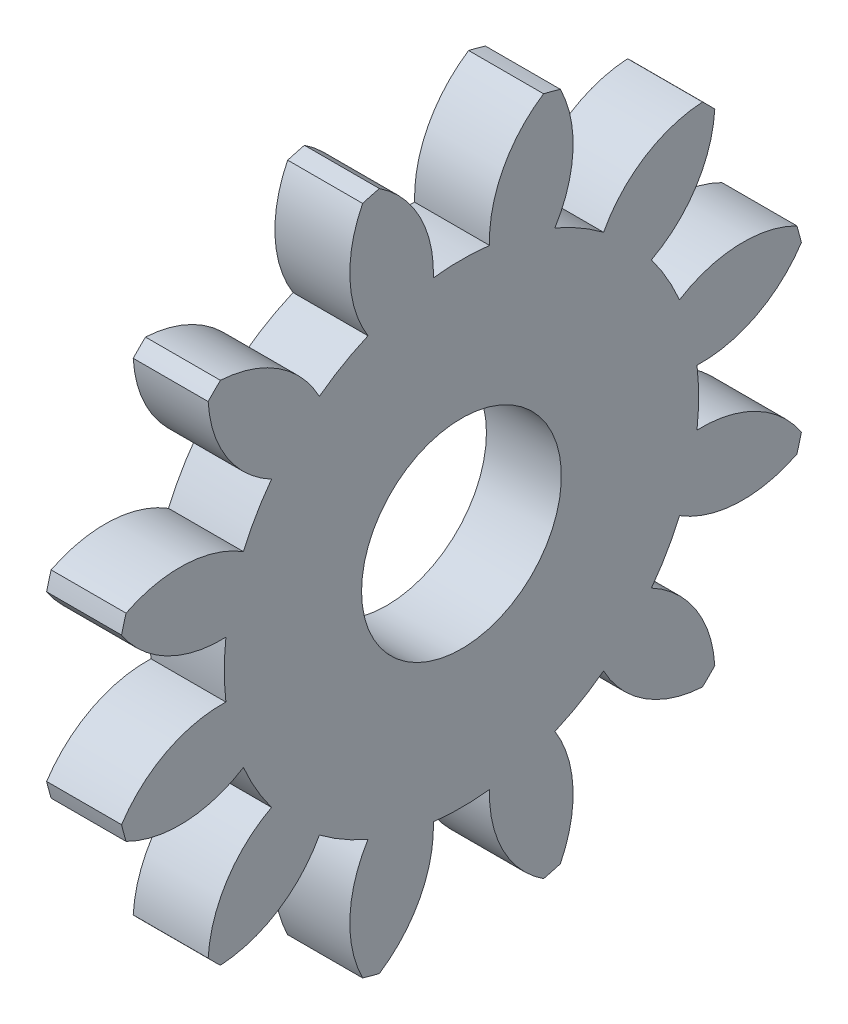
SolidWorks part; units mm, degrees
material "Zinc AC41A Alloy, As Cast"
ref_plane "Plane1" through (0, 0, 0) normal (0, 0, 1) x (1, 0, 0)
ref_plane "Plane2" through (0, 0, 0) normal (0, 1, 0) x (1, 0, 0)
ref_plane "Plane3" through (0, 0, 0) normal (1, 0, 0) x (0, 0, -1)
sketch "HoldingSke" plane through (0, 0, 0) normal (0, 1, 0) x (1, 0, 0)
  line L0 (0, 0) -> (0.9781, -0.2079)
  line L1 (-15, 0) -> (100, 0) construction
  line L2 (0, 0) -> (-2.1039, 2.3779)
  line L3 (0, 0) -> (-11.863, 4.5341)
  line L4 (0, 0) -> (8.4473, 1.7955)
  line L5 (0, 0) -> (-46.8476, -17.4728)
  line L6 (0, 0) -> (-1.2434, -0.839)
  line L7 (-2.1039, 2.3779) -> (8.6586, 51.2059)
  line L8 (-76.2, 54.61) -> (-75.5, 54.61)
  line L9 (-71.009, 38.7566) -> (-53.1078, 45.2721)
  line L10 (-76.2, 71.12) -> (104.1128, 71.12)
  line L11 (0, 0) -> (-1.5, 0)
  line L12 (-76.2, 101.6) -> (-76.162, 101.6)
  line L13 (24.9733, 27.94) -> (52.9518, 28.4284)
  line L14 (24.9733, 27.94) -> (24.9743, 27.94)
  line L15 (24.9733, 27.94) -> (100.4006, 29.5858)
  line L16 (-63.627, -1) -> (-12.827, -1)
  circle A0 centre (0, 0) radius 2
  circle A1 centre (0, 0) radius 4.749
  circle A2 centre (0, 0) radius 37.5
  circle A3 centre (0, 0) radius 2
  dimension "MHD" = 9.498
  dimension "Hub_dia" = 75
  dimension "Bore" = 4
  dimension "MBD" = 4
  dimension "Num_teeth" = 12
  dimension "Pitch" = 1
  dimension "Overall_len" = 50
  dimension "Show_teeth" = 12
  dimension "Thickness" = 1.5
  dimension "OAL" = 50.0001
  dimension "T_dim" = 0.7
  dimension "Ap" = 20
  dimension "H" = 19.05
  dimension "Pitch_radius" = 180.3128
  dimension "Width" = 1.5
  dimension "Backlash" = 0.038
  dimension "Addendum_fac" = 1
  dimension "Dedendum_fac" = 1.25
  dimension "Clearance_fac" = 0.25
  dimension "Dedendum_add" = 0.001
  dimension "Module" = 1
sketch "BasProSke" plane through (0, 0, 0) normal (0, 1, 0) x (1, 0, 0)
  line L0 (-10, 0) -> (60, 0) construction
  line L1 (0, 0) -> (0, 7)
  line L2 (0, 0) -> (1.5, 0)
  line L3 (1.5, 0) -> (1.5, 7)
  line L4 (1.5, 7) -> (0, 7)
  dimension "Thickness" = 1.5
  dimension "Diameter" = 14
revolve "Base-Revolve" add sketch "BasProSke" angle 360 about L0
sketch "TooCutSke" plane through (0, 0, 0) normal (1, 0, 0) x (0, 0, -1)
  line L1 (0, 0) -> (0, 107) construction
  line L2 (0, 0) -> (-0.8496, 5.9395) construction
  line L3 (0, 0) -> (-3.0836, 11.5081) construction
  line L4 (-0.8496, 5.9395) -> (-1.5418, 5.7541) construction
  arc A0 (0.5622, 4.7156) -> (-0.5622, 4.7156) centre (0, 0) ccw
  arc A1 (1.6729, 6.8233) -> (-1.6729, 6.8233) centre (0, 0) ccw
  circle A2 centre (0, 0) radius 6 construction
  circle A3 centre (0, 0) radius 5.6382 construction
  arc A4 (-0.5622, 4.7156) -> (-1.6729, 6.8233) centre (-2.9608, 4.7982) ccw
  arc A5 (1.6729, 6.8233) -> (0.5622, 4.7156) centre (2.9608, 4.7982) ccw
  dimension "Root_dia" = 9.498
  dimension "Overcut_dia" = 14.0508
  dimension "Pitch_dia" = 12
  dimension "Base_dia" = 11.2763
  dimension "Flank_rad" = 2.4
  dimension "Half_ang" = 15
  dimension "Half_CT" = 0.7167
extrude "ToothCut" cut sketch "TooCutSke" along normal through all
fillet "Breaks" [suppressed] radius 0.02
fillet "RootFillets" [suppressed] radius 0.251
pattern_circular "TeethCuts" count 12 every 30 about axis through (-10, 0, 0) along (1, 0, 0) of "ToothCut", "RootFillets", "Breaks"
sketch "HubNeaOneSke" plane through (0, 0, 0) normal (-1, 0, 0) x (0, 0, 1)
  circle A0 centre (0, 0) radius 4.749
  dimension "Diameter" = 9.498
extrude "HubNearOne" [suppressed] add sketch "HubNeaOneSke" along normal blind 48.5001
sketch "HubNeaBotSke" plane through (0, 0, 0) normal (-1, 0, 0) x (0, 0, 1)
  circle A0 centre (0, 0) radius 4.749
  dimension "Diameter" = 9.498
extrude "HubNearBoth" [suppressed] add sketch "HubNeaBotSke" along normal blind 24.25
ref_plane "FarPln" through (1.5, 0, 0) normal (1, 0, 0) x (0, 0, -1)
sketch "HubFarSke" plane through (1.5, 0, 0) normal (1, 0, 0) x (0, 0, -1)
  circle A0 centre (0, 0) radius 4.749
  dimension "Diameter" = 9.498
extrude "HubFar" [suppressed] add sketch "HubFarSke" along normal blind 24.25
sketch "BorSke" plane through (0, 0, 0) normal (1, 0, 0) x (0, 0, -1)
  circle A0 centre (0, 0) radius 2
  dimension "Diameter" = 4
extrude "Bore" cut sketch "BorSke" along normal mid plane 100.0001
sketch "KeySke" plane through (0, 0, 0) normal (1, 0, 0) x (0, 0, -1)
  line L0 (-0.8, 0) -> (-0.8, 2.7)
  line L1 (-0.8, 2.7) -> (0.8, 2.7)
  line L2 (0.8, 2.7) -> (0.8, 0)
  line L3 (0, 0) -> (0, 34) construction
  line L4 (-0.8, 0) -> (0.8, 0)
  dimension "Offset" = 2.7
  dimension "Width" = 1.6
extrude "Keyway" [suppressed] cut sketch "KeySke" along normal mid plane 100.0001
pattern_circular "Keyway2" [suppressed] count 2 every 90 about axis through (-10, 0, 0) along (1, 0, 0)
equation "' \"Module@HoldingSke\" = 6.35"
equation "' \"Num_teeth@HoldingSke\" = 12"
equation "' \"Ap@HoldingSke\" =  20"
equation "' \"Ap@HoldingSke\" = 20"
equation "' \"Width@HoldingSke\" = 0.5 * 25.4"
equation "' \"Hub_dia@HoldingSke\"= 1 * 25.4"
equation "' \"Hub_dia@HoldingSke\" = 1 * 25.4"
equation "' \"Overall_len@HoldingSke\" = 1.0 * 25.4"
equation "' \"Bore@HoldingSke\" = 0.75 * 25.4"
equation "' \"T_dim@HoldingSke\" = 0.1 * 25.4"
equation "' \"Width@KeySke\" = 0.25 * 25.4"
equation "' \"Show_teeth@HoldingSke\" = 13"
equation "' \"Backlash@HoldingSke\" = 0.009 * 25.4"
equation "' \"Addendum_fac@HoldingSke\" = 1.0"
equation "' \"Dedendum_fac@HoldingSke\" = 1.25"
equation "' \"Dedendum_add@HoldingSke\" = 0.00005 * 25.4"
equation "' \"Clearance_fac@HoldingSke\" = 0.25"
equation "\"Pitch@HoldingSke\" = 1 / \"Module@HoldingSke\""
equation "\"Overcut_dia@TooCutSke\" = (\"Num_teeth@HoldingSke\" + 2 * \"Addendum_fac@HoldingSke\") / \"Pitch@HoldingSke\" + 0.002 * 25.4"
equation "\"Pitch_dia@TooCutSke\" = \"Num_teeth@HoldingSke\" / \"Pitch@HoldingSke\""
equation "\"Base_dia@TooCutSke\" = \"Num_teeth@HoldingSke\" / \"Pitch@HoldingSke\" * cos((\"Ap@HoldingSke\"  * 3.14159265 / 180))"
equation "\"Root_dia@TooCutSke\" = (\"Num_teeth@HoldingSke\" + 2) / \"Pitch@HoldingSke\" - 2 * (\"Addendum_fac@HoldingSke\" + \"Dedendum_fac@HoldingSke\") / \"Pitch@HoldingSke\" - \"Dedendum_add@HoldingSke\" * 2"
equation "\"Half_ang@TooCutSke\" = 180 / \"Num_teeth@HoldingSke\""
equation "\"Half_CT@TooCutSke\" = \"Num_teeth@HoldingSke\" / \"Pitch@HoldingSke\" * sin((3.14159265 / 2 / \"Num_teeth@HoldingSke\")) / 2 - 7 * \"Backlash@HoldingSke\" / 4"
equation "\"Flank_rad@TooCutSke\" = \"Num_teeth@HoldingSke\" / \"Pitch@HoldingSke\" / 5"
equation "\"Radius@RootFillets\" = \"Clearance_fac@HoldingSke\" / \"Pitch@HoldingSke\" + \"Dedendum_add@HoldingSke\""
equation "\"Break_rad@Breaks\" = 0.02 / \"Pitch@HoldingSke\""
equation "\"Thickness@HoldingSke\" = \"Width@HoldingSke\""
equation "\"OAL@HoldingSke\" = \"Thickness@HoldingSke\""
equation "\"MHD@HoldingSke\" = (\"Num_teeth@HoldingSke\" + 2) / \"Pitch@HoldingSke\" - 2 * (\"Addendum_fac@HoldingSke\" + \"Dedendum_fac@HoldingSke\")  / \"Pitch@HoldingSke\" - \"Dedendum_add@HoldingSke\" * 2"
equation "\"MBD@HoldingSke\" = (\"Num_teeth@HoldingSke\" + 2) / \"Pitch@HoldingSke\" - 2 * (\"Addendum_fac@HoldingSke\" + \"Dedendum_fac@HoldingSke\")  / \"Pitch@HoldingSke\" - \"Dedendum_add@HoldingSke\" * 2 - 0.002 * 25.4"
equation "\"MHD@HoldingSke\" = ((sgn( \"MHD@HoldingSke\" - \"Hub_dia@HoldingSke\" )-1)*( \"MHD@HoldingSke\" - \"Hub_dia@HoldingSke\" ))/-2+ \"Hub_dia@HoldingSke\""
equation "\"MBD@HoldingSke\" = ((sgn( \"MBD@HoldingSke\" - \"Bore@HoldingSke\" )-1)*( \"MBD@HoldingSke\" - \"Bore@HoldingSke\" ))/-2+ \"Bore@HoldingSke\""
equation "\"OAL@HoldingSke\" = ((sgn( \"OAL@HoldingSke\" - \"Overall_len@HoldingSke\" )+1)*( \"OAL@HoldingSke\" - \"Overall_len@HoldingSke\" ))/2 + \"Overall_len@HoldingSke\" + 0.000002 * 25.4"
equation "\"Num_teeth@TeethCuts\" = int( \"Show_teeth@HoldingSke\" ) + 1"
equation "\"Num_teeth@TeethCuts\" = ((sgn( \"Num_teeth@TeethCuts\" - \"Num_teeth@HoldingSke\" )-1)*( \"Num_teeth@TeethCuts\" - \"Num_teeth@HoldingSke\" ))/-2+ \"Num_teeth@HoldingSke\""
equation "\"Num_teeth@TeethCuts\" = ((sgn( \"Num_teeth@TeethCuts\" - 2.0)+1)*( \"Num_teeth@TeethCuts\" - 2.0))/2 +2.0"
equation "\"Angle@TeethCuts\" = 360.0 / \"Num_teeth@HoldingSke\""
equation "\"Diameter@BasProSke\" = (\"Num_teeth@HoldingSke\" + 2 * \"Addendum_fac@HoldingSke\") / \"Pitch@HoldingSke\""
equation "\"Thickness@BasProSke\"  = \"Thickness@HoldingSke\""
equation "' \"Fillet_rad@BasProSke\" =  \"Thickness@HoldingSke\" * 0.05"
equation "' \"Fillet_rad@BasProSke\" = \"Thickness@HoldingSke\" * 0.05"
equation "\"MHD@HoldingSke\" = ((sgn( \"MHD@HoldingSke\" - \"Root_dia@TooCutSke\" )-1)*( \"MHD@HoldingSke\" - \"Root_dia@TooCutSke\" ))/-2+ \"Root_dia@TooCutSke\""
equation "\"Diameter@HubNeaOneSke\" = \"MHD@HoldingSke\""
equation "\"Length@HubNearOne\" = \"OAL@HoldingSke\" - \"Thickness@BasProSke\""
equation "\"Diameter@HubNeaBotSke\" = \"MHD@HoldingSke\""
equation "\"Length@HubNearBoth\" = ( \"OAL@HoldingSke\" - \"Thickness@BasProSke\" ) / 2.0"
equation "\"Thickness@FarPln\" = \"Thickness@BasProSke\""
equation "\"Diameter@HubFarSke\" = \"MHD@HoldingSke\""
equation "\"Length@HubFar\" = ( \"OAL@HoldingSke\" - \"Thickness@BasProSke\" ) / 2.0"
equation "\"Diameter@BorSke\" = \"MBD@HoldingSke\""
equation "\"D1@Bore\" = \"OAL@HoldingSke\" * 2.0"
equation "\"D1@Keyway\" = \"OAL@HoldingSke\" * 2.0"
equation "\"Offset@KeySke\" = \"T_dim@HoldingSke\" + \"MBD@HoldingSke\" / 2.0"
